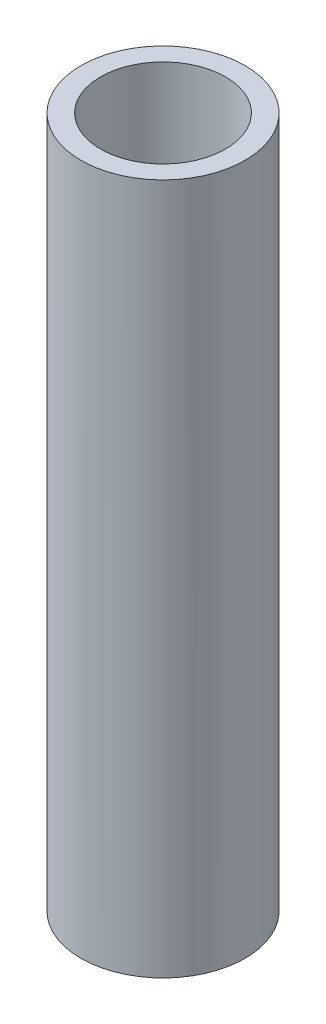
SolidWorks part; units mm, degrees
material "AISI 316 Stainless Steel Sheet (SS)"
ref_plane "Front Plane" through (0, 0, 0) normal (0, 0, 1) x (1, 0, 0)
ref_plane "Top Plane" through (0, 0, 0) normal (0, 1, 0) x (1, 0, 0)
ref_plane "Right Plane" through (0, 0, 0) normal (1, 0, 0) x (0, 0, -1)
sketch "Sketch1" plane through (0, 0, 0) normal (0, 1, 0) x (1, 0, 0)
  circle A0 centre (0, 0) radius 1.05
  circle A1 centre (0, 0) radius 0.8
  dimension "D1" = 2.1
  dimension "D2" = 1.6
extrude "Boss-Extrude1" add sketch "Sketch1" along normal offset from surface (8.841 mm away) 4 contours A1 | A0
